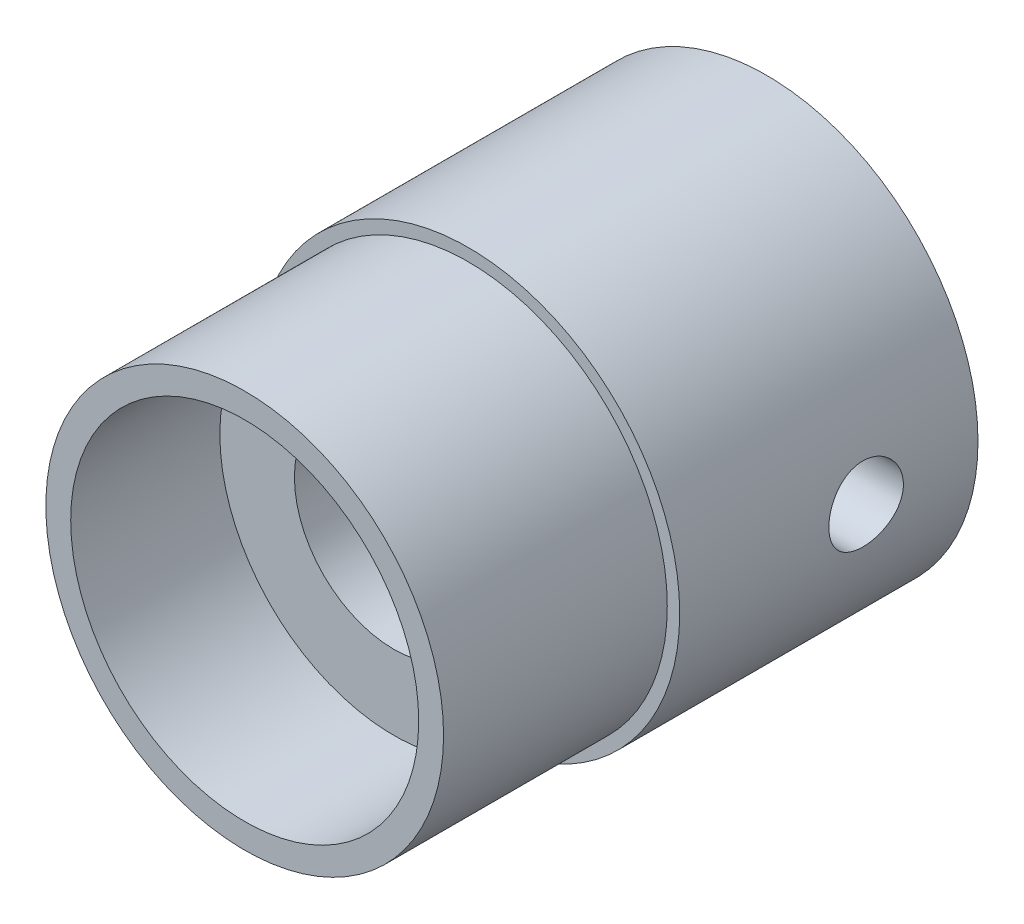
SolidWorks part; units mm, degrees
ref_plane "Front Plane" through (0, 0, 0) normal (0, 0, 1) x (1, 0, 0)
ref_plane "Top Plane" through (0, 0, 0) normal (0, 1, 0) x (1, 0, 0)
ref_plane "Right Plane" through (0, 0, 0) normal (1, 0, 0) x (0, 0, -1)
sketch "Sketch1" plane through (0, 0, 0) normal (0, 0, 1) x (1, 0, 0)
  circle A0 centre (0, 0) radius 7.5
  circle A1 centre (0, 0) radius 4
  dimension "D1" = 15
  dimension "D2" = 8
extrude "Boss-Extrude1" add sketch "Sketch1" along normal blind 3
sketch "Sketch2" plane through (0, 0, 0) normal (0, 0, 1) x (1, 0, 0)
  circle A0 centre (0, 0) radius 5.5
  circle A1 centre (0, 0) radius 8.5
  dimension "D1" = 11
  dimension "D2" = 3
extrude "Boss-Extrude2" add sketch "Sketch2" against normal blind 12
sketch "Sketch4" plane through (0, 0, 0) normal (1, 0, 0) x (0, 0, -1)
  line L0 (12, -8.5) -> (12, 8.5) construction
  circle A0 centre (7.5, 0) radius 1.5
  dimension "D1" = 3
  dimension "D2" = 4.5
extrude "Cut-Extrude1" cut sketch "Sketch4" against normal through all both and the other way through all
sketch "Sketch5" plane through (0, 0, 3) normal (0, 0, 1) x (1, 0, 0)
  circle A0 centre (0, 0) radius 8
  circle A1 centre (0, 0) radius 7
  dimension "D1" = 16
  dimension "D2" = 14
extrude "Boss-Extrude4" add sketch "Sketch5" along normal blind 6 and the other way blind 3
